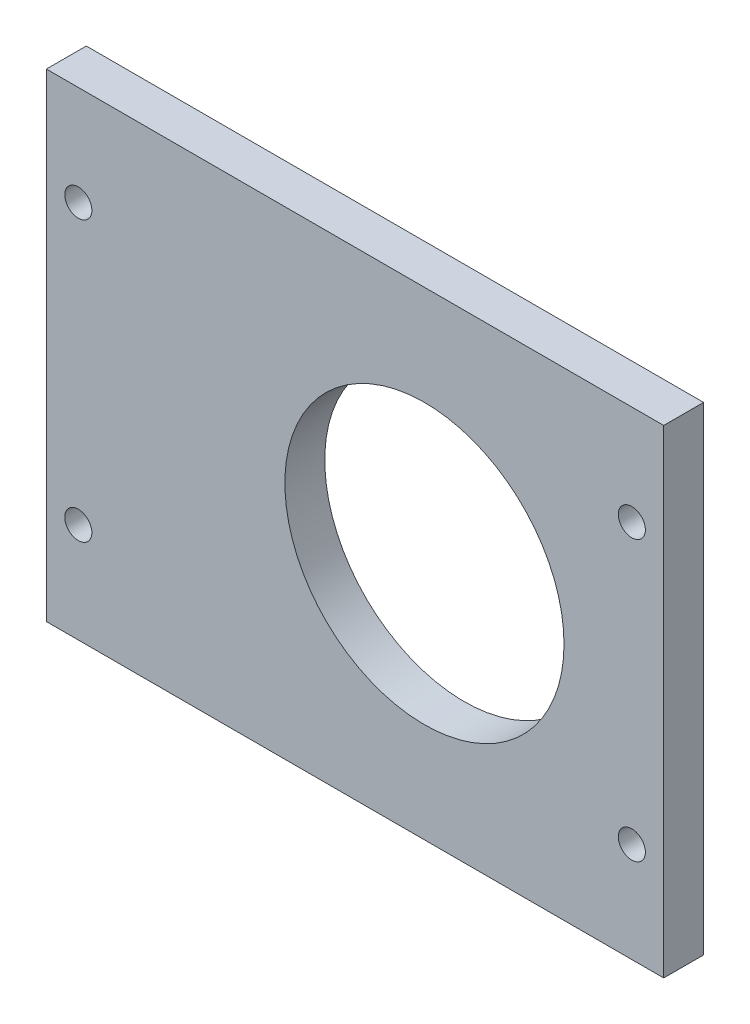
SolidWorks part; units mm, degrees
material "2024-T3"
ref_plane "正面" through (0, 0, 0) normal (0, 0, 1) x (1, 0, 0)
ref_plane "平面" through (0, 0, 0) normal (0, 1, 0) x (1, 0, 0)
ref_plane "右側面" through (0, 0, 0) normal (1, 0, 0) x (0, 0, -1)
sketch "ｽｹｯﾁ1" plane through (0, 0, 0) normal (0, 0, 1) x (1, 0, 0)
  line L1 (0, 0) -> (77.4, 0)
  line L2 (0, 0) -> (0, 60)
  line L3 (0, 60) -> (77.4, 60)
  line L4 (77.4, 0) -> (77.4, 60)
  dimension "D1" = 60
  dimension "D2" = 77.4
extrude "ﾎﾞｽ - 押し出し1" add sketch "ｽｹｯﾁ1" along normal blind 5
sketch "ｽｹｯﾁ2" plane through (0, 0, 5) normal (0, 0, 1) x (1, 0, 0)
  line L0 (0, 0) -> (77.4, 0) construction
  line L2 (77.4, 0) -> (77.4, 60) construction
  circle A0 centre (47.4, 30) radius 17.5
  dimension "D1" = 35
  dimension "D2" = 30
  dimension "D3" = 30
extrude "ｶｯﾄ - 押し出し1" cut sketch "ｽｹｯﾁ2" against normal through all contours A0
hole_wizard "Ø3.4 (3.4) 直径の穴2" positions "3Dｽｹｯﾁ2" profile "ｽｹｯﾁ5" hole size "Ø3.4" standard "JIS" end condition through all
sketch3d "3Dｽｹｯﾁ2"
  line L0 (77.4, 60, 5) -> (0, 60, 5) construction
  line L1 (77.4, 0, 5) -> (77.4, 60, 5) construction
  line L2 (0, 0, 5) -> (77.4, 0, 5) construction
  line L3 (0, 60, 5) -> (0, 0, 5) construction
  point P0 (73.4, 47.5, 5)
  point P2 (73.4, 12.5, 5)
  point P4 (4, 12.5, 5)
  point P6 (4, 47.5, 5)
  dimension "D1" = 12.5
  dimension "D2" = 4
  dimension "D3" = 4
  dimension "D4" = 12.5
  dimension "D5" = 12.5
  dimension "D6" = 4
  dimension "D7" = 4
  dimension "D8" = 12.5
sketch "ｽｹｯﾁ5" plane through (73.4, 47.5, 5) normal (1, 0, 0) x (0, -1, 0)
  line L0 (0, 0) -> (0, 5)
  line L1 (0, 5) -> (1.7, 5)
  line L2 (1.7, 5) -> (1.7, 0)
  line L5 (1.7, 0) -> (0, 0)
  line L11 (0, -6.35) -> (0, 107.95) construction
  dimension "通し穴の直径" = 3.4
  dimension "通し穴の深さ" = 5
